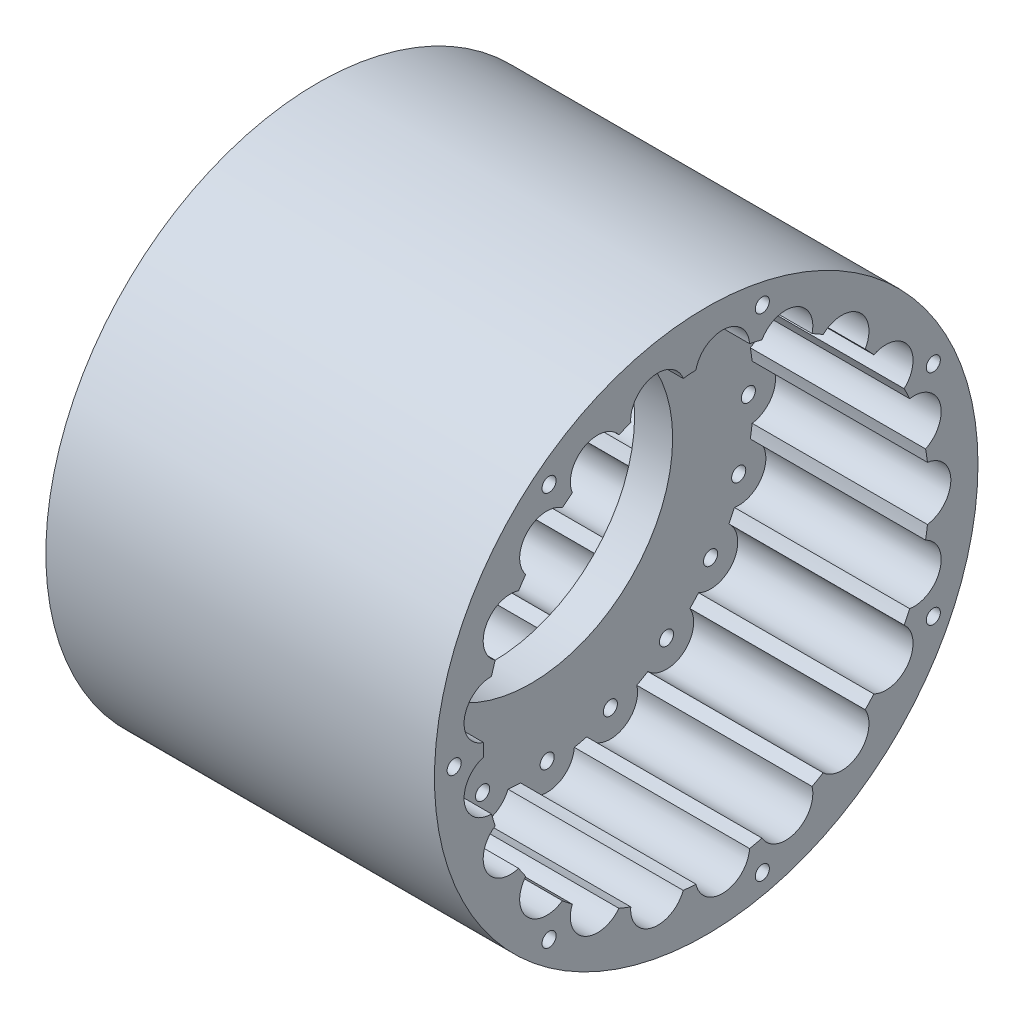
SolidWorks part; units mm, degrees
ref_plane "Ebene vorne" through (0, 0, 0) normal (0, 0, 1) x (1, 0, 0)
ref_plane "Ebene oben" through (0, 0, 0) normal (0, 1, 0) x (1, 0, 0)
ref_plane "Ebene rechts" through (0, 0, 0) normal (1, 0, 0) x (0, 0, -1)
sketch "Skizze2" plane through (0, 0, 0) normal (0, 0, 1) x (1, 0, 0)
  line L0 (0, 0) -> (-33680.1149, 0) construction
  line L1 (0, 26.075) -> (3.5, 26.075)
  line L2 (3.5, 26.075) -> (3.5, 41)
  line L3 (3.5, 41) -> (35.75, 41)
  line L4 (35.75, 41) -> (35.75, 50)
  line L5 (35.75, 50) -> (0, 50)
  line L6 (0, 50) -> (0, 26.075)
  line L7 (0, 0) -> (0, 50000) construction
  dimension "D1" = 52.15
  dimension "D2" = 3.5
  dimension "D3" = 35.75
  dimension "D4" = 100
  dimension "D5" = 82
revolve "Rotation1" add sketch "Skizze2" angle 360 about L0
sketch "Skizze4" plane through (35.75, 0, 0) normal (1, 0, 0) x (0, 0, -1)
  line L0 (0, 0) -> (-50000, 0) construction
  circle A6 centre (0, 0) radius 40 construction
  circle A7 centre (40, 0) radius 5
  circle A8 centre (38.2229, -11.7902) radius 5
  circle A9 centre (33.0496, -22.5328) radius 5
  circle A10 centre (24.9396, -31.2733) radius 5
  circle A11 centre (14.6136, -37.2349) radius 5
  circle A12 centre (2.9892, -39.8882) radius 5
  circle A13 centre (-8.9008, -38.9971) radius 5
  circle A14 centre (-20, -34.641) radius 5
  circle A15 centre (-29.3221, -27.2069) radius 5
  circle A16 centre (-36.0388, -17.3553) radius 5
  circle A17 centre (-39.5532, -5.9617) radius 5
  circle A18 centre (-39.5532, 5.9617) radius 5
  circle A19 centre (-36.0388, 17.3553) radius 5
  circle A20 centre (-29.3221, 27.2069) radius 5
  circle A21 centre (-20, 34.641) radius 5
  circle A22 centre (-8.9008, 38.9971) radius 5
  circle A23 centre (2.9892, 39.8882) radius 5
  circle A24 centre (14.6136, 37.2349) radius 5
  circle A25 centre (24.9396, 31.2733) radius 5
  circle A26 centre (33.0496, 22.5328) radius 5
  circle A27 centre (38.2229, 11.7902) radius 5
  point P49 (0, 0)
  dimension "D2" = 10
  dimension "D3" = 21
extrude "Schnitt-Linear austragen1" cut sketch "Skizze4" against normal up to surface (32.25 mm away) up to face at (3.5, 0, -41)
sketch "Skizze5" plane through (35.75, 0, 0) normal (1, 0, 0) x (0, 0, -1)
  line L0 (0, 0) -> (-50000, 0) construction
  circle A0 centre (-46.3698, 0) radius 1.3
  circle A1 centre (-28.9111, 36.2534) radius 1.3
  circle A2 centre (10.3183, 45.2073) radius 1.3
  circle A3 centre (41.7778, 20.1191) radius 1.3
  circle A4 centre (41.7778, -20.1191) radius 1.3
  circle A5 centre (10.3183, -45.2073) radius 1.3
  circle A6 centre (-28.9111, -36.2534) radius 1.3
  point P20 (0, 0)
  dimension "D1" = 2.6
  dimension "D2" = 7
extrude "Schnitt-Linear austragen2" cut sketch "Skizze5" against normal blind 13
mirror "Spiegeln1" about plane through (0, 0, 0) normal (1, 0, 0) of "Schnitt-Linear austragen2", "Schnitt-Linear austragen1", "Rotation1"
hole_wizard "Ø2.6 (2.6) Durchmesser Bohrung1" positions "Skizze6" profile "Skizze7" hole size "Ø2.6" standard "ISO" end condition through all
sketch "Skizze6" plane through (3.5, 0, 0) normal (1, 0, 0) x (0, 0, -1)
  point P0 (40, 0)
sketch "Skizze7" plane through (3.5, 0, -40) normal (0, 1, 0) x (0, 0, -1)
  line L0 (0, 0) -> (0, 39.25)
  line L1 (0, 39.25) -> (1.3, 39.25)
  line L2 (1.3, 39.25) -> (1.3, 0)
  line L5 (1.3, 0) -> (0, 0)
  line L11 (0, -6.35) -> (0, 107.95) construction
  dimension "Bohrerdurchmesser" = 2.6
  dimension "Bohrungstiefe" = 39.25
pattern_circular "Kreismuster1" count 21 over 360 about axis through (0, 0, 0) along (1, 0, 0) of "Ø2.6 (2.6) Durchmesser Bohrung1"
